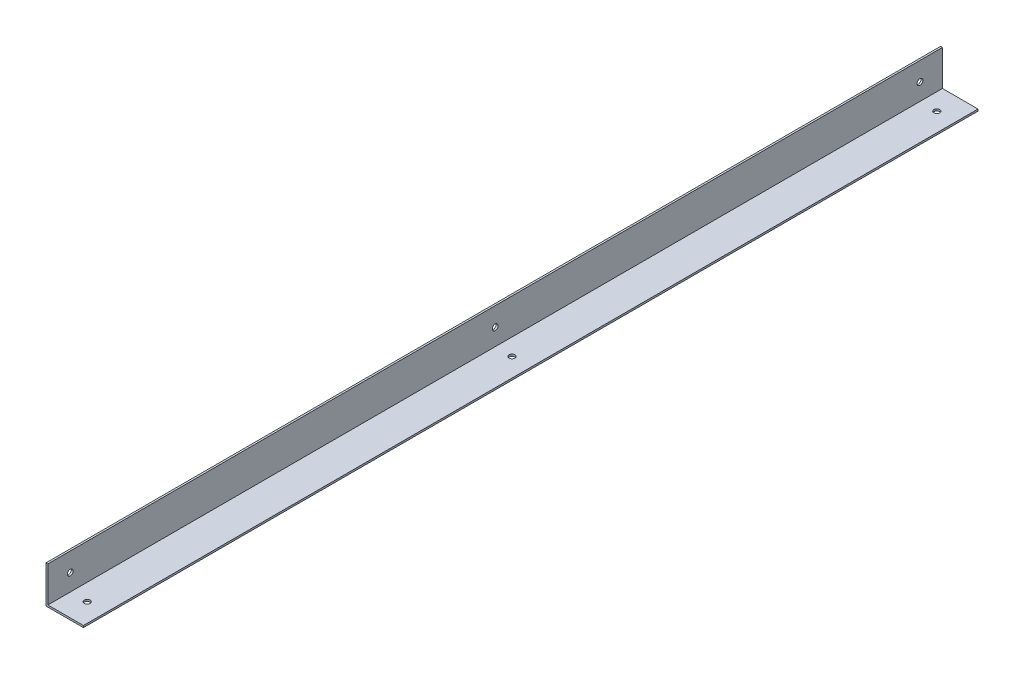
SolidWorks part; units mm, degrees
material "1060 Alloy"
ref_plane "Front Plane" through (0, 0, 0) normal (0, 0, 1) x (1, 0, 0)
ref_plane "Top Plane" through (0, 0, 0) normal (0, 1, 0) x (1, 0, 0)
ref_plane "Right Plane" through (0, 0, 0) normal (1, 0, 0) x (0, 0, -1)
sketch "Sketch2" plane through (0, 0, 0) normal (0, 0, 1) x (1, 0, 0)
  line L0 (0, 0) -> (0, 31.75)
  line L1 (0, 31.75) -> (1.5875, 31.75)
  line L2 (1.5875, 31.75) -> (1.5875, 1.5875)
  line L3 (1.5875, 1.5875) -> (31.75, 1.5875)
  line L4 (31.75, 1.5875) -> (31.75, 0)
  line L5 (31.75, 0) -> (0, 0)
  dimension "D1" = 31.75
  dimension "D2" = 1.5875
  dimension "D3" = 30.1625
  dimension "D4" = 31.75
extrude "Boss-Extrude1" add sketch "Sketch2" along normal blind 758.825
sketch "Sketch3" plane through (0, 0, 0) normal (-1, 0, 0) x (0, 0, 1)
  line L0 (379.4125, 31.75) -> (379.4125, 0) construction
  line L1 (758.825, 31.75) -> (0, 31.75) construction
  line L2 (758.825, 0) -> (0, 0) construction
  line L3 (0, 15.875) -> (758.825, 15.875) construction
  line L4 (0, 31.75) -> (0, 0) construction
  line L5 (758.825, 31.75) -> (758.825, 0) construction
hole_wizard "#10 (0.1935) Diameter Hole1" positions "Sketch4" profile "Sketch5" hole size "#10" standard "ANSI Inch" end condition through all
sketch "Sketch4" plane through (0, 0, 0) normal (-1, 0, 0) x (0, 0, 1)
  line L0 (0, 15.875) -> (758.825, 15.875) construction
  line L1 (379.4125, 31.75) -> (379.4125, 0) construction
  line L2 (758.825, 31.75) -> (758.825, 0) construction
  line L3 (0, 31.75) -> (0, 0) construction
  point P0 (19.05, 15.875)
  point P4 (379.4125, 15.875)
  point P8 (739.775, 15.875)
  dimension "D1" = 19.05
  dimension "D2" = 19.05
sketch "Sketch5" plane through (0, 15.875, 19.05) normal (0, 1, 0) x (0, 0, 1)
  line L0 (0, 0) -> (0, 31.75)
  line L1 (0, 31.75) -> (2.4574, 31.75)
  line L2 (2.4574, 31.75) -> (2.4574, 0)
  line L5 (2.4574, 0) -> (0, 0)
  line L11 (0, -6.35) -> (0, 107.95) construction
  dimension "Thru Hole Dia." = 4.9149
  dimension "Thru Hole Depth" = 31.75
hole_wizard "#10 (0.1935) Diameter Hole3" positions "Sketch6" profile "Sketch7" hole size "#10" standard "ANSI Inch" end condition through all
sketch "Sketch6" plane through (0, 0, 0) normal (0, -1, 0) x (-1, 0, 0)
  line L0 (-15.875, 0) -> (-15.875, -758.825) construction
  line L1 (0, 0) -> (-31.75, 0) construction
  line L2 (0, -758.825) -> (-31.75, -758.825) construction
  line L4 (0, -379.4125) -> (-31.75, -379.4125) construction
  line L5 (0, -758.825) -> (0, 0) construction
  line L6 (-31.75, -758.825) -> (-31.75, 0) construction
  point P15 (-15.875, -379.4125)
  point P17 (-15.875, -19.05)
  point P19 (-15.875, -739.775)
  dimension "D1" = 19.05
  dimension "D2" = 19.05
sketch "Sketch7" plane through (15.875, 0, 739.775) normal (1, 0, 0) x (0, 0, -1)
  line L0 (0, 0) -> (0, 31.75)
  line L1 (0, 31.75) -> (2.4574, 31.75)
  line L2 (2.4574, 31.75) -> (2.4574, 0)
  line L5 (2.4574, 0) -> (0, 0)
  line L11 (0, -6.35) -> (0, 107.95) construction
  dimension "Thru Hole Dia." = 4.9149
  dimension "Thru Hole Depth" = 31.75
